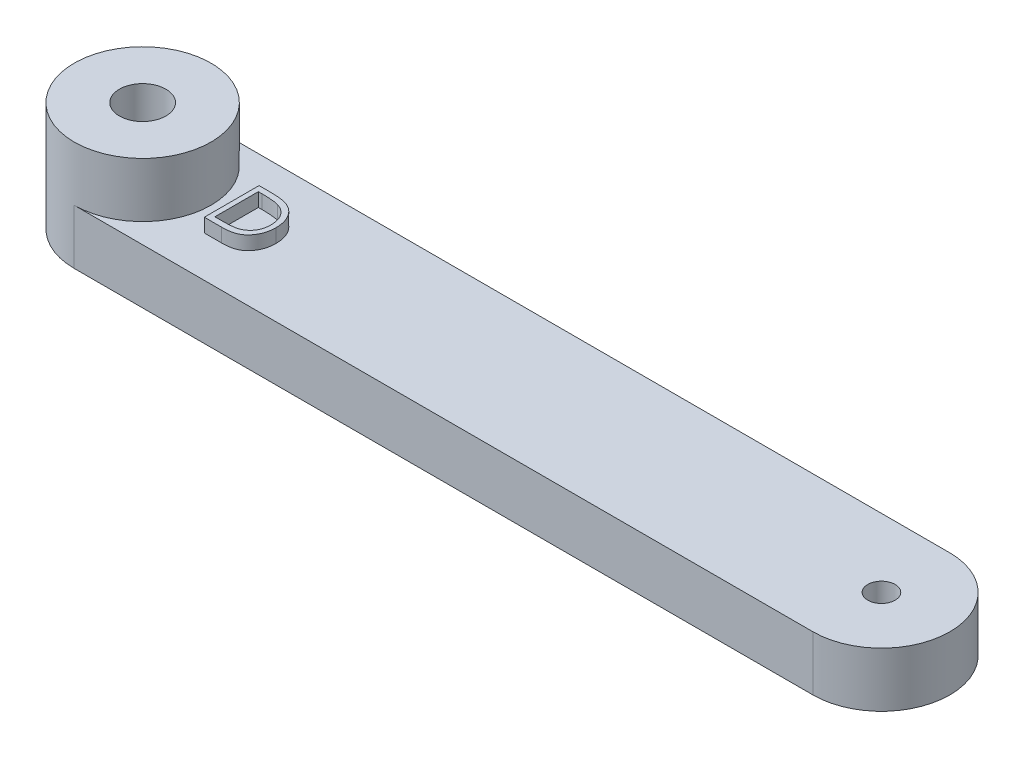
SolidWorks part; units mm, degrees
ref_plane "Plano frontal" through (0, 0, 0) normal (0, 0, 1) x (1, 0, 0)
ref_plane "Plano superior" through (0, 0, 0) normal (0, 1, 0) x (1, 0, 0)
ref_plane "Plano direito" through (0, 0, 0) normal (1, 0, 0) x (0, 0, -1)
sketch "Esboço1" plane through (0, 0, 0) normal (0, 1, 0) x (1, 0, 0)
  line L0 (-13.5, 0) -> (13.5, 0) construction
  line L1 (-13.5, 2.5) -> (13.5, 2.5)
  line L2 (-13.5, -2.5) -> (13.5, -2.5)
  arc A0 (-13.5, 2.5) -> (-13.5, -2.5) centre (-13.5, 0) ccw
  arc A1 (13.5, -2.5) -> (13.5, 2.5) centre (13.5, 0) ccw
  point P3 (0, 0)
  dimension "D1" = 27
  dimension "D2" = 5
extrude "Ressalto-extrusão1" add sketch "Esboço1" along normal blind 2
sketch "Esboço4" plane through (0, 2, 0) normal (0, 1, 0) x (1, 0, 0)
  circle A0 centre (-13.5, 0) radius 2.5
  arc A1 (-13.5, 2.5) -> (-13.5, -2.5) centre (-13.5, 0) ccw construction
extrude "Ressalto-extrusão2" add sketch "Esboço4" along normal blind 2
sketch "Esboço2" plane through (0, 4, 0) normal (0, 1, 0) x (1, 0, 0)
  circle A0 centre (-13.5, 0) radius 0.85
  arc A1 (-13.5, -2.5) -> (-13.5, 2.5) centre (-13.5, 0) ccw construction
  dimension "D1" = 1.7
extrude "Corte-extrusão1" cut sketch "Esboço2" against normal through all
sketch "Esboço3" plane through (0, 2, 0) normal (0, 1, 0) x (1, 0, 0)
  circle A0 centre (13.5, 0) radius 0.5
  arc A1 (13.5, -2.5) -> (13.5, 2.5) centre (13.5, 0) ccw construction
  dimension "D1" = 1
extrude "Corte-extrusão2" cut sketch "Esboço3" against normal up to next
sketch "Esboço5" plane through (0, 2, 0) normal (0, 1, 0) x (1, 0, 0)
  line L0 (-8.188, -1) -> (-10.7651, -1) construction
  line L1 (-13.5, -2.5) -> (13.5, -2.5) construction
  text T0 "D" font "Century Gothic" height 2
  dimension "D1" = 1.5
extrude "Ressalto-extrusão3" add sketch "Esboço5" along normal blind 0.5
